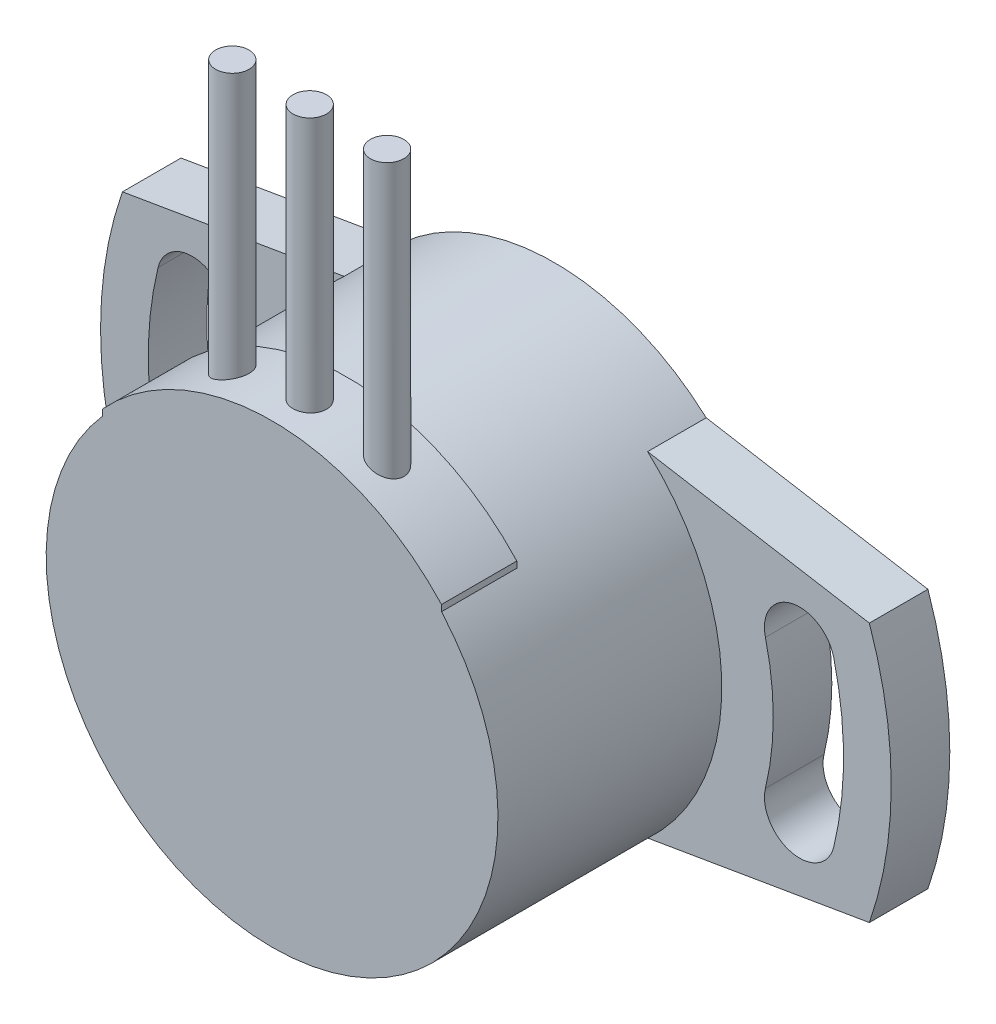
SolidWorks part; units mm, degrees
ref_plane "Front" through (0, 0, 0) normal (0, 0, 1) x (1, 0, 0)
ref_plane "Top" through (0, 0, 0) normal (0, 1, 0) x (1, 0, 0)
ref_plane "Right" through (0, 0, 0) normal (1, 0, 0) x (0, 0, -1)
sketch "Sketch1" plane through (0, 0, 0) normal (0, 0, 1) x (1, 0, 0)
  circle A0 centre (0, 0) radius 13.716
  dimension "D1" = 27.432
extrude "Boss-Extrude1" add sketch "Sketch1" along normal blind 13.589
sketch "Sketch2" plane through (0, 0, 0) normal (0, 0, -1) x (-1, 0, 0)
  line L0 (-22.6747, 7.874) -> (-9.2143, 10.16)
  line L1 (-22.6747, -7.874) -> (-9.2143, -10.16)
  line L2 (0, 0) -> (-24.003, 0) construction
  circle A0 centre (0, 0) radius 24.003
  circle A1 centre (0, 0) radius 13.716 construction
  dimension "D1" = 48.006
  dimension "D2" = 20.32
  dimension "D3" = 10.16
  dimension "D4" = 15.748
extrude "Boss-Extrude2" add sketch "Sketch2" along normal blind 3.556
sketch "Sketch3" plane through (0, 0, -3.556) normal (0, 0, -1) x (-1, 0, 0)
  line L0 (-22.6747, 7.874) -> (-9.2143, 10.16) construction
  line L1 (-22.6747, -7.874) -> (-9.2143, -10.16) construction
  circle A0 centre (0, 0) radius 21.1074
  circle A1 centre (0, 0) radius 16.8402
  arc A2 (-22.6747, 7.874) -> (-22.6747, -7.874) centre (0, 0) ccw construction
  circle A3 centre (-18.4395, 4.4711) radius 2.1336
  circle A4 centre (-18.4395, -4.4711) radius 2.1336
  dimension "D1" = 2.8956
  dimension "D2" = 4.2672
  dimension "D3" = 4.064
  dimension "D4" = 4.064
extrude "Cut-Extrude1" cut sketch "Sketch3" against normal blind 3.556 contours A3 | A4 A1 A3 A0 | A4
mirror "Mirror1" about plane through (0, 0, 0) normal (1, 0, 0) of "Boss-Extrude2", "Cut-Extrude1"
sketch "Sketch4" plane through (0, 0, -3.556) normal (0, 0, -1) x (-1, 0, 0)
  circle A0 centre (0, 0) radius 4.953
  dimension "D1" = 9.906
extrude "Boss-Extrude3" add sketch "Sketch4" along normal blind 4.826
sketch "Sketch5" plane through (0, 0, -8.382) normal (0, 0, -1) x (-1, 0, 0)
  circle A0 centre (0, 0) radius 3.0162
  dimension "D1" = 6.0325
extrude "Cut-Extrude2" cut sketch "Sketch5" against normal blind 2.54
sketch "Sketch7" plane through (0, 0, 13.589) normal (0, 0, 1) x (1, 0, 0)
  line L0 (10.287, 9.4519) -> (10.287, 5.9516)
  line L1 (10.287, 5.9516) -> (-10.287, 5.9516)
  line L2 (-10.287, 5.9516) -> (-10.287, 9.4519)
  line L3 (0, 0) -> (0, 13.97) construction
  circle A0 centre (0, 0) radius 13.97
  circle A1 centre (0, 0) radius 13.716 construction
  circle M4 centre (0, 0) radius 13.716
  dimension "D1" = 0.254
  dimension "D2" = 20.574
extrude "Boss-Extrude4" add sketch "Sketch7" against normal blind 4.572 contours L1 L3 L2 M4 | L3 L1 L0 M4 | L3 A0 L2 M4 | L3 L0 A0 M4
sketch "Sketch6" plane through (0, 0, 0) normal (0, 1, 0) x (1, 0, 0)
  line L0 (0, 0) -> (0, -11.303) construction
  line L1 (-13.716, -13.589) -> (13.716, -13.589) construction
  line L2 (-4.699, -11.303) -> (4.699, -11.303) construction
  circle A0 centre (0, -11.303) radius 1.016
  circle A1 centre (-4.699, -11.303) radius 1.016
  circle A2 centre (4.699, -11.303) radius 1.016
  dimension "D1" = 2.032
  dimension "D2" = 2.286
  dimension "D3" = 9.398
extrude "Boss-Extrude5" add sketch "Sketch6" along normal blind 29.464
